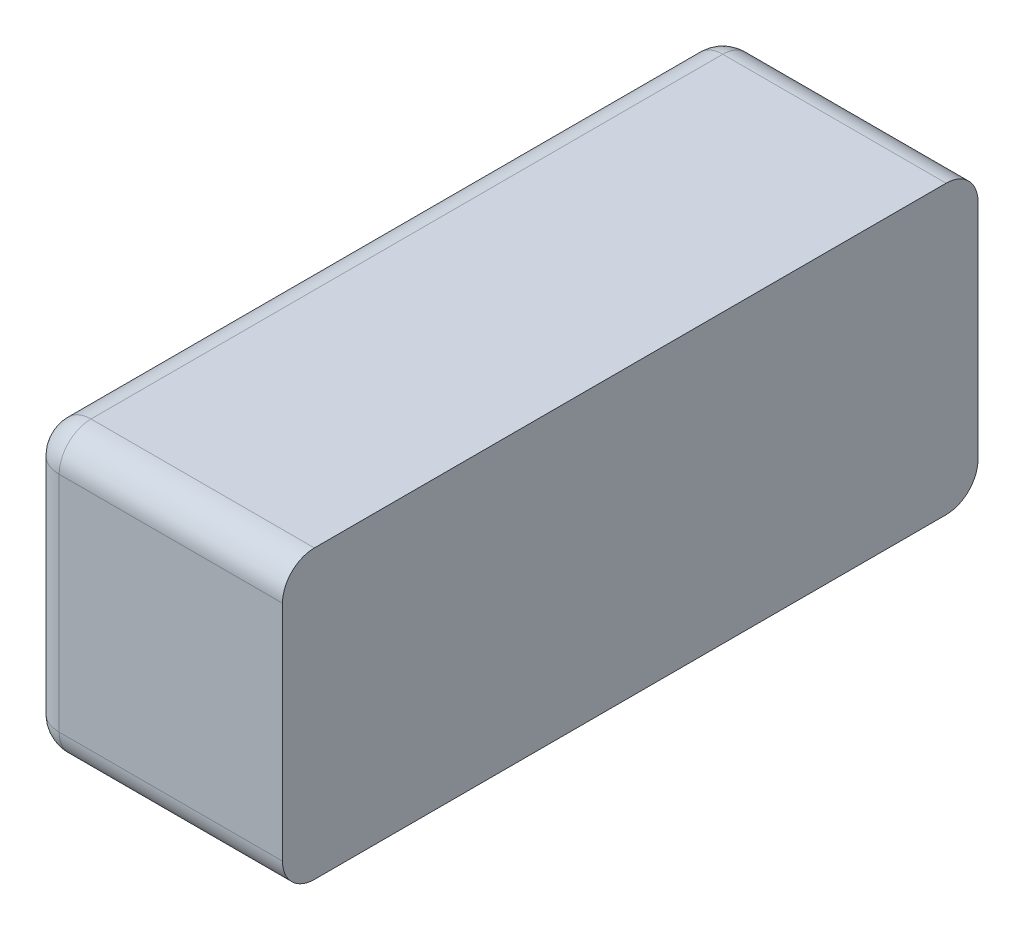
SolidWorks part; units mm, degrees
ref_plane "前视基准面" through (0, 0, 0) normal (0, 0, 1) x (1, 0, 0)
ref_plane "上视基准面" through (0, 0, 0) normal (0, 1, 0) x (1, 0, 0)
ref_plane "右视基准面" through (0, 0, 0) normal (1, 0, 0) x (0, 0, -1)
other "Configuration Table"
sketch "草图1" plane through (0, 0, 0) normal (0, 0, 1) x (1, 0, 0)
  line L0 (-25.7143, -22.5) -> (14.2857, -22.5)
  line L1 (14.2857, -22.5) -> (14.2857, 22.5)
  line L2 (14.2857, 22.5) -> (-25.7143, 22.5)
  line L3 (-25.7143, 22.5) -> (-25.7143, -22.5)
  dimension "D1" = 45
  dimension "D2" = 40
extrude "80横向_70纵向_70竖向" add sketch "草图1" along normal blind 109
fillet "圆角2" radius 5 8 edges at (-5.7143, -22.5, 0) (-5.7143, 22.5, 0) (-5.7143, -22.5, 109) (-5.7143, 22.5, 109) (-25.7143, 0, 109) (-25.7143, 0, 0) (-25.7143, -22.5, 54.5) (-25.7143, 22.5, 54.5)
